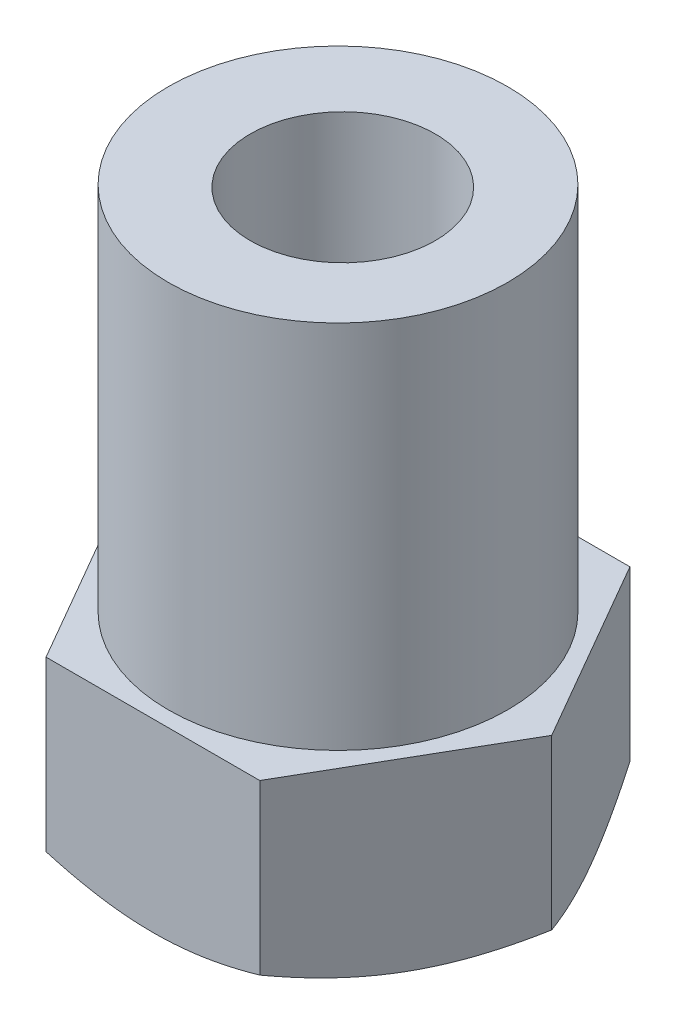
SolidWorks part; units mm, degrees
material "黄铜"
ref_plane "前视" through (0, 0, 0) normal (0, 0, 1) x (1, 0, 0)
ref_plane "上视" through (0, 0, 0) normal (0, 1, 0) x (1, 0, 0)
ref_plane "右视" through (0, 0, 0) normal (1, 0, 0) x (0, 0, -1)
sketch "草图1" plane through (0, 0, 0) normal (0, 1, 0) x (1, 0, 0)
  line L1 (6.9282, 0) -> (3.4641, 6)
  line L2 (3.4641, 6) -> (-3.4641, 6)
  line L3 (-3.4641, 6) -> (-6.9282, 0)
  line L4 (-6.9282, 0) -> (-3.4641, -6)
  line L5 (-3.4641, -6) -> (3.4641, -6)
  line L6 (3.4641, -6) -> (6.9282, 0)
  circle A0 centre (0, 0) radius 6 construction
  dimension "D1" = 12
extrude "凸台-拉伸1" add sketch "草图1" along normal blind 6
sketch "草图2" plane through (0, 6, 0) normal (0, 1, 0) x (1, 0, 0)
  circle A0 centre (0, 0) radius 5.5
  dimension "D1" = 11
extrude "凸台-拉伸2" add sketch "草图2" along normal blind 12
sketch "草图3" plane through (0, 18, 0) normal (0, 1, 0) x (1, 0, 0)
  circle A0 centre (0.1549, 0) radius 3
  dimension "D1" = 6
extrude "切除-拉伸1" cut sketch "草图3" against normal through all
sketch "草图4" plane through (0, 0, 0) normal (0, -1, 0) x (1, 0, 0)
  circle A0 centre (0, 0) radius 6
extrude "切除-拉伸2" cut sketch "草图4" against normal blind 10 draft 60 flip side to cut
